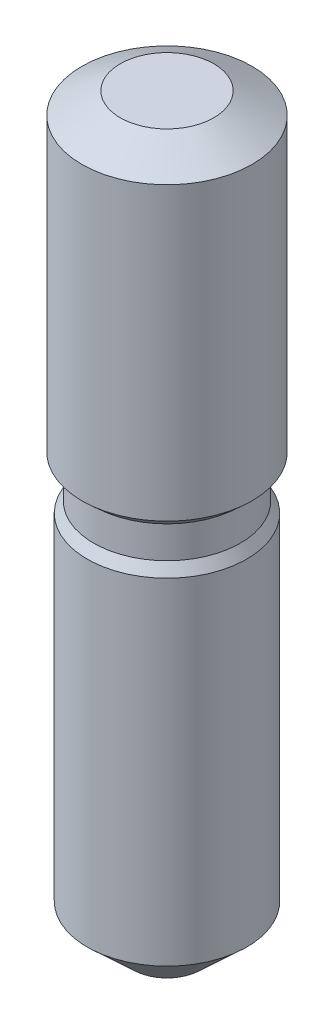
SolidWorks part; units mm, degrees
ref_plane "Alzado" through (0, 0, 0) normal (0, 0, 1) x (1, 0, 0)
ref_plane "Planta" through (0, 0, 0) normal (0, 1, 0) x (1, 0, 0)
ref_plane "Vista lateral" through (0, 0, 0) normal (1, 0, 0) x (0, 0, -1)
sketch "Sketch1" plane through (0, 0, 0) normal (0, 0, 1) x (1, 0, 0)
  line L0 (0, 0) -> (4.4, 0)
  line L1 (4.4, 0) -> (8, -2)
  line L2 (8, -2) -> (8, -29.4)
  line L3 (8, -29.4) -> (6.9, -30.4)
  line L4 (6.9, -30.4) -> (6.9, -33.4)
  line L5 (6.9, -33.4) -> (7.5, -34.4)
  line L6 (7.5, -34.4) -> (7.5, -66)
  line L7 (7.5, -66) -> (3.2, -70)
  line L8 (3.2, -70) -> (0, -70)
  line L9 (0, -70) -> (0, 0)
  line L10 (0, -74) -> (0, 4) construction
revolve "Motor_reductora_husillo" add sketch "Sketch1" angle 360 about L10
